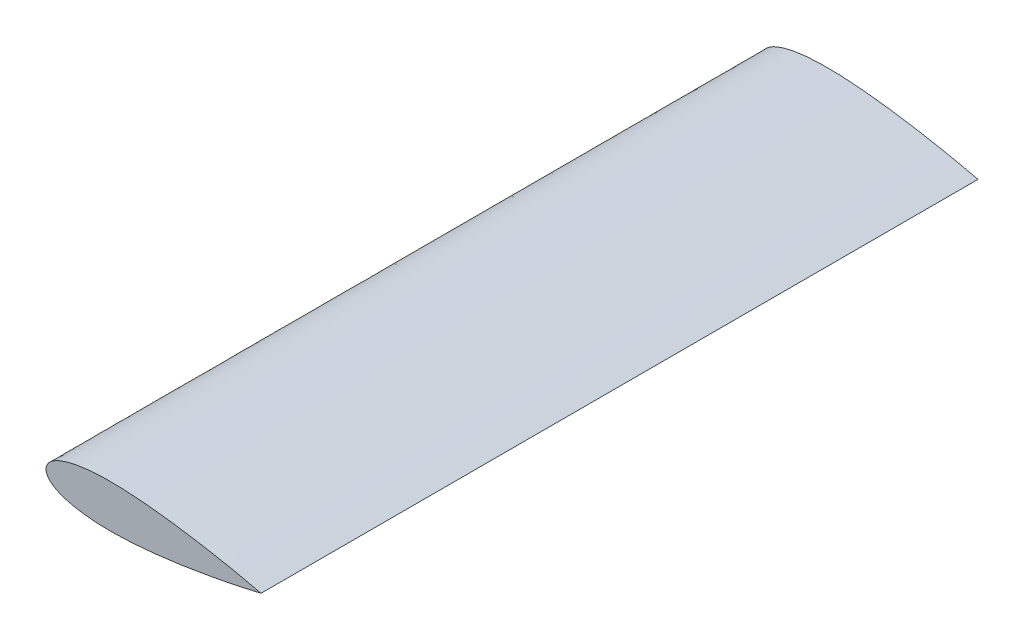
SolidWorks part; units mm, degrees
ref_plane "前视基准面" through (0, 0, 0) normal (0, 0, 1) x (1, 0, 0)
ref_plane "上视基准面" through (0, 0, 0) normal (0, 1, 0) x (1, 0, 0)
ref_plane "右视基准面" through (0, 0, 0) normal (1, 0, 0) x (0, 0, -1)
sketch "草图2" plane through (0, 0, 0) normal (0, 0, 1) x (1, 0, 0)
  spline S0 degree 4 poles (0, 0) (-0.0002, 0.507) (0.0449, 1.3817) (0.226, 2.6508) (0.688, 4.3) (1.3355, 5.873) (2.267, 7.5426) (3.5719, 9.3461) (5.3914, 11.3247) (7.9545, 13.5395) (11.585, 16.0215) (16.6481, 18.727) (23.7932, 21.6498) (33.0858, 24.4369) (46.6431, 27.2845) (64.0632, 29.3627) (84.4508, 30.2603) (107.4149, 29.86) (130.3326, 28.4283) (153.1861, 26.2148) (175.9708, 23.3917) (195.8486, 20.4876) (212.8449, 17.733) (226.9805, 15.2709) (238.2713, 13.2039) (248.1352, 11.3101) (256.5773, 9.6255) (263.6047, 8.1795) (269.2198, 6.9974) (274.131, 5.9394) (278.332, 5.0171) (281.8385, 4.235) (284.6266, 3.6061) (287.4466, 2.9621) (290.2003, 2.3266) (293.0761, 1.6538) (295.7002, 1.0342) (299.1487, 0.2076) (301.6998, -0.4115) (305.9289, -1.45) (309.2336, -2.281) (313.2598, -3.3026) (316.8434, -4.2332) (320.6976, -5.2459) (323.9028, -6.1065) (326.7456, -6.8783) (328.5968, -7.3881) (329.5319, -7.6468) (330.0005, -7.7768) knots 0 0 0 0 0 0.005875 0.010168 0.014828 0.019835 0.025575 0.032309 0.04061 0.050967 0.064812 0.083253 0.107121 0.14043 0.177264 0.243882 0.3105 0.377118 0.443736 0.510354 0.576972 0.64359 0.676899 0.710208 0.743517 0.776826 0.793481 0.810135 0.82679 0.843444 0.851772 0.860099 0.868426 0.876753 0.885081 0.893408 0.901735 0.910062 0.921305 0.932547 0.943789 0.955031 0.966273 0.977516 0.988758 0.994379 1 1 1 1 1 construction
  spline S1 degree 4 poles (0, 0) (-0.0002, 0.507) (0.0449, 1.3817) (0.226, 2.6508) (0.688, 4.3) (1.3355, 5.873) (2.267, 7.5426) (3.5719, 9.3461) (5.3914, 11.3247) (7.9545, 13.5395) (11.585, 16.0215) (16.6481, 18.727) (23.7932, 21.6498) (33.0858, 24.4369) (46.6431, 27.2845) (64.0632, 29.3627) (84.4508, 30.2603) (107.4149, 29.86) (130.3326, 28.4283) (153.1861, 26.2148) (175.9708, 23.3917) (195.8486, 20.4876) (212.8449, 17.733) (226.9805, 15.2709) (238.2713, 13.2039) (248.1352, 11.3101) (256.5773, 9.6255) (263.6047, 8.1795) (269.2198, 6.9974) (274.131, 5.9394) (278.332, 5.0171) (281.8385, 4.235) (284.6266, 3.6061) (287.4466, 2.9621) (290.2003, 2.3266) (293.0761, 1.6538) (295.7002, 1.0342) (298.0785, 0.4641) (299.3655, 0.1537) (300, 0) knots 0 0 0 0 0 0.005875 0.010168 0.014828 0.019835 0.025575 0.032309 0.04061 0.050967 0.064812 0.083253 0.107121 0.14043 0.177264 0.243882 0.3105 0.377118 0.443736 0.510354 0.576972 0.64359 0.676899 0.710208 0.743517 0.776826 0.793481 0.810135 0.82679 0.843444 0.851772 0.860099 0.868426 0.876753 0.885081 0.893408 0.901735 0.910062 0.910062 0.910062 0.910062 0.910062
  spline S2 degree 4 poles (0, 0) (-0.0002, -0.507) (0.0449, -1.3817) (0.226, -2.6508) (0.688, -4.3) (1.3355, -5.873) (2.267, -7.5426) (3.5719, -9.3461) (5.3914, -11.3247) (7.9545, -13.5395) (11.585, -16.0215) (16.6481, -18.727) (23.7932, -21.6498) (33.0858, -24.4369) (46.6431, -27.2845) (64.0632, -29.3627) (84.4508, -30.2603) (107.4149, -29.86) (130.3326, -28.4283) (153.1861, -26.2148) (175.9708, -23.3917) (195.8486, -20.4876) (212.8449, -17.733) (226.9805, -15.2709) (238.2713, -13.2039) (248.1352, -11.3101) (256.5773, -9.6255) (263.6047, -8.1795) (269.2198, -6.9974) (274.131, -5.9394) (278.332, -5.0171) (281.8385, -4.235) (284.6266, -3.6061) (287.4466, -2.9621) (290.2003, -2.3266) (293.0761, -1.6538) (295.7002, -1.0342) (299.1487, -0.2076) (301.6998, 0.4115) (305.9289, 1.45) (309.2336, 2.281) (313.2598, 3.3026) (316.8434, 4.2332) (320.6976, 5.2459) (323.9028, 6.1065) (326.7456, 6.8783) (328.5968, 7.3881) (329.5319, 7.6468) (330.0005, 7.7768) knots 0 0 0 0 0 0.005875 0.010168 0.014828 0.019835 0.025575 0.032309 0.04061 0.050967 0.064812 0.083253 0.107121 0.14043 0.177264 0.243882 0.3105 0.377118 0.443736 0.510354 0.576972 0.64359 0.676899 0.710208 0.743517 0.776826 0.793481 0.810135 0.82679 0.843444 0.851772 0.860099 0.868426 0.876753 0.885081 0.893408 0.901735 0.910062 0.921305 0.932547 0.943789 0.955031 0.966273 0.977516 0.988758 0.994379 1 1 1 1 1 construction
  spline S3 degree 4 poles (0, 0) (-0.0002, -0.507) (0.0449, -1.3817) (0.226, -2.6508) (0.688, -4.3) (1.3355, -5.873) (2.267, -7.5426) (3.5719, -9.3461) (5.3914, -11.3247) (7.9545, -13.5395) (11.585, -16.0215) (16.6481, -18.727) (23.7932, -21.6498) (33.0858, -24.4369) (46.6431, -27.2845) (64.0632, -29.3627) (84.4508, -30.2603) (107.4149, -29.86) (130.3326, -28.4283) (153.1861, -26.2148) (175.9708, -23.3917) (195.8486, -20.4876) (212.8449, -17.733) (226.9805, -15.2709) (238.2713, -13.2039) (248.1352, -11.3101) (256.5773, -9.6255) (263.6047, -8.1795) (269.2198, -6.9974) (274.131, -5.9394) (278.332, -5.0171) (281.8385, -4.235) (284.6266, -3.6061) (287.4466, -2.9621) (290.2003, -2.3266) (293.0761, -1.6538) (295.7002, -1.0342) (298.0785, -0.4641) (299.3655, -0.1537) (300, 0) knots 0 0 0 0 0 0.005875 0.010168 0.014828 0.019835 0.025575 0.032309 0.04061 0.050967 0.064812 0.083253 0.107121 0.14043 0.177264 0.243882 0.3105 0.377118 0.443736 0.510354 0.576972 0.64359 0.676899 0.710208 0.743517 0.776826 0.793481 0.810135 0.82679 0.843444 0.851772 0.860099 0.868426 0.876753 0.885081 0.893408 0.901735 0.910062 0.910062 0.910062 0.910062 0.910062
  point P0 (-105.6934, 10.506)
extrude "凸台-拉伸1" add sketch "草图2" along normal blind 1000
